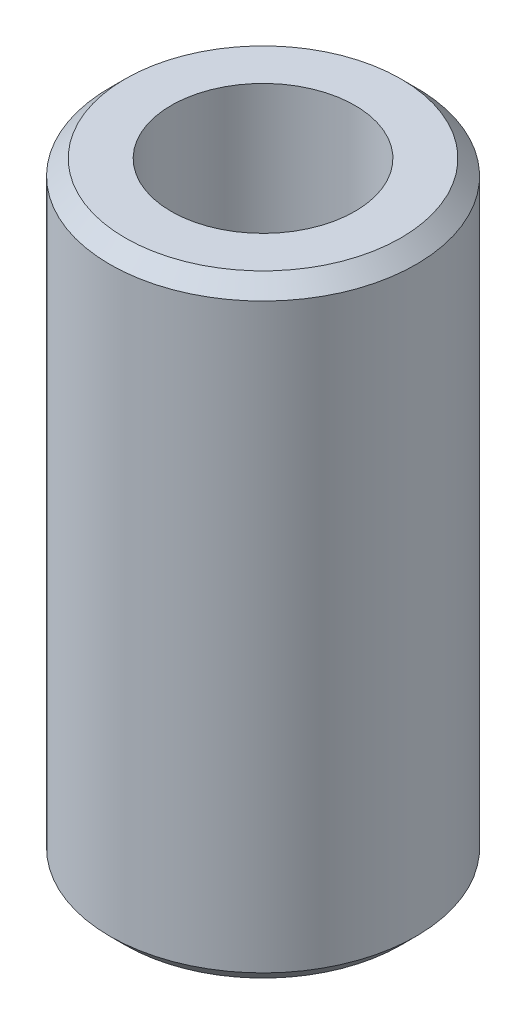
SolidWorks part; units mm, degrees
ref_plane "Front Plane" through (0, 0, 0) normal (0, 0, 1) x (1, 0, 0)
ref_plane "Top Plane" through (0, 0, 0) normal (0, 1, 0) x (1, 0, 0)
ref_plane "Right Plane" through (0, 0, 0) normal (1, 0, 0) x (0, 0, -1)
sketch "Sketch1" plane through (0, 0, 0) normal (0, 1, 0) x (1, 0, 0)
  circle A0 centre (0, 0) radius 5
  circle A1 centre (0, 0) radius 3
  dimension "D1" = 10
  dimension "D2" = 6
extrude "Boss-Extrude1" add sketch "Sketch1" along normal mid plane 20
chamfer "Chamfer1" distance 0.5 angle 45 2 edges at (0, -10, 5) (0, 10, 5)
